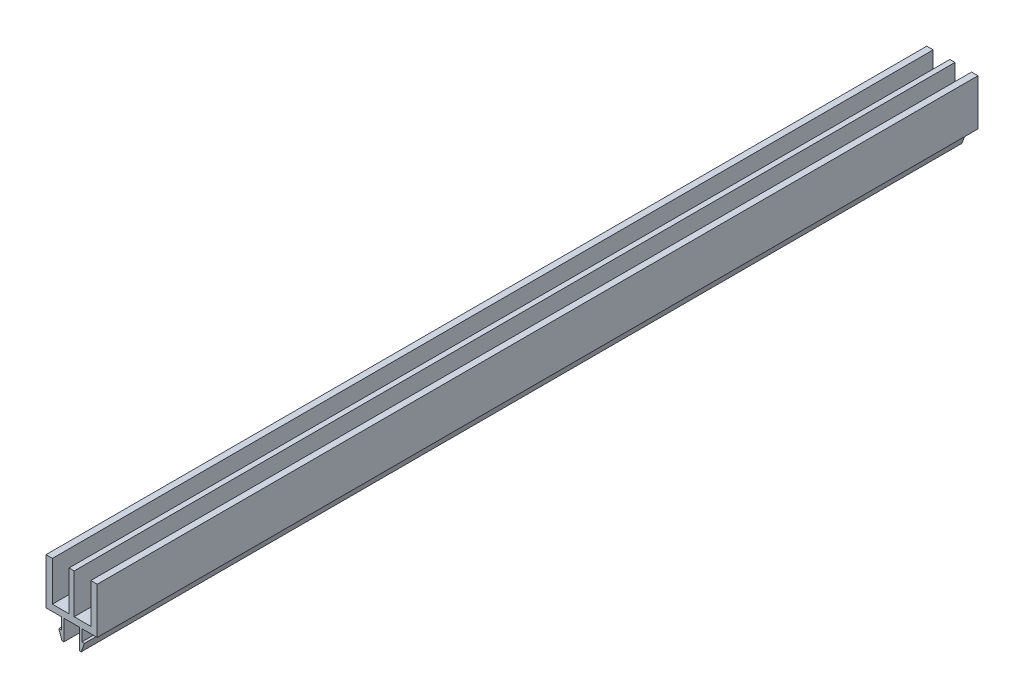
SolidWorks part; units mm, degrees
ref_plane "Plan de face" through (0, 0, 0) normal (0, 0, 1) x (1, 0, 0)
ref_plane "Plan de dessus" through (0, 0, 0) normal (0, 1, 0) x (1, 0, 0)
ref_plane "Plan de droite" through (0, 0, 0) normal (1, 0, 0) x (0, 0, -1)
ref_plane "Plan1" through (0, 0, 50) normal (0, 0, 1) x (1, 0, 0)
sketch "Esquisse1" plane through (0, 0, 50) normal (0, 0, 1) x (1, 0, 0)
  line L0 (-1, 2.5) -> (-7.5, 2.5)
  line L1 (-7.5, 2.5) -> (-7.5, 18)
  line L2 (-7.5, 18) -> (-10, 18)
  line L3 (-10, 18) -> (-10, 0)
  line L4 (-10, 0) -> (-4, 0)
  line L5 (-4, 0) -> (-4, -4.5)
  line L6 (-4, -4.5) -> (-5, -4.5)
  line L7 (-5, -4.5) -> (-3.75, -8)
  line L8 (-3.75, -8) -> (-3, -8)
  line L9 (-3, -8) -> (-3, 0)
  line L10 (-3, 0) -> (3, 0)
  line L11 (3, 0) -> (3, -8)
  line L12 (3, -8) -> (3.75, -8)
  line L13 (3.75, -8) -> (5, -4.5)
  line L14 (5, -4.5) -> (4, -4.5)
  line L15 (4, -4.5) -> (4, 0)
  line L16 (4, 0) -> (10, 0)
  line L17 (10, 0) -> (10, 18)
  line L18 (10, 18) -> (7.5, 18)
  line L19 (7.5, 18) -> (7.5, 2.5)
  line L20 (7.5, 2.5) -> (1, 2.5)
  line L21 (1, 2.5) -> (1, 18)
  line L22 (1, 18) -> (-1, 18)
  line L23 (-1, 18) -> (-1, 2.5)
extrude "Boss.-Extru.1" add sketch "Esquisse1" against normal blind 344
